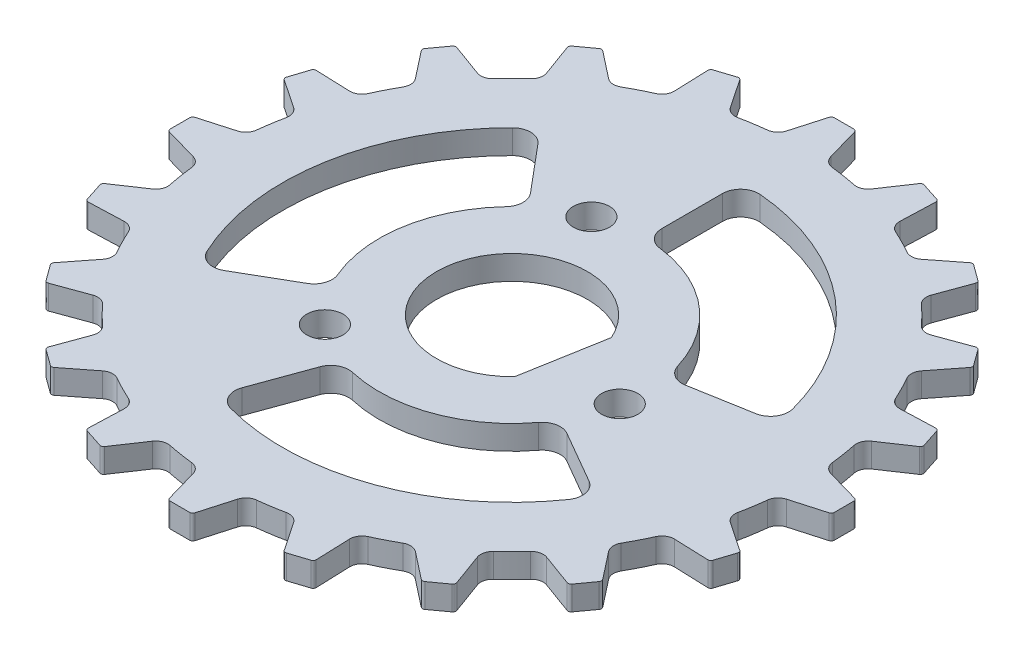
SolidWorks part; units mm, degrees
ref_plane "Front" through (0, 0, 0) normal (0, 0, 1) x (1, 0, 0)
ref_plane "Top" through (0, 0, 0) normal (0, 1, 0) x (1, 0, 0)
ref_plane "Right" through (0, 0, 0) normal (1, 0, 0) x (0, 0, -1)
sketch "草图1" plane through (0, 0, 0) normal (0, 1, 0) x (1, 0, 0)
  line L0 (-0.8114, 27.5) -> (0.8114, 27.5)
  line L3 (1.8377, 24.5681) -> (1.0518, 27.3187)
  line L7 (-1.8377, 24.5681) -> (-1.0518, 27.3187)
  line L8 (7.7263, 26.4048) -> (9.2697, 25.9033)
  line L9 (9.3397, 22.7977) -> (9.4423, 25.6566)
  line L10 (5.8442, 23.9335) -> (7.4416, 26.3066)
  line L11 (15.5076, 22.7249) -> (16.8206, 21.771)
  line L12 (15.9275, 18.7958) -> (16.9084, 21.483)
  line L13 (12.954, 20.9562) -> (15.2066, 22.7195)
  line L14 (21.771, 16.8206) -> (22.7249, 15.5076)
  line L15 (20.9562, 12.954) -> (22.7195, 15.2066)
  line L16 (18.7958, 15.9275) -> (21.483, 16.9084)
  line L17 (25.9033, 9.2697) -> (26.4048, 7.7263)
  line L18 (23.9335, 5.8442) -> (26.3066, 7.4416)
  line L19 (22.7977, 9.3397) -> (25.6566, 9.4423)
  line L20 (27.5, 0.8114) -> (27.5, -0.8114)
  line L21 (24.5681, -1.8377) -> (27.3187, -1.0518)
  line L22 (24.5681, 1.8377) -> (27.3187, 1.0518)
  line L23 (26.4048, -7.7263) -> (25.9033, -9.2697)
  line L24 (22.7977, -9.3397) -> (25.6566, -9.4423)
  line L25 (23.9335, -5.8442) -> (26.3066, -7.4416)
  line L26 (22.7249, -15.5076) -> (21.771, -16.8206)
  line L27 (18.7958, -15.9275) -> (21.483, -16.9084)
  line L28 (20.9562, -12.954) -> (22.7195, -15.2066)
  line L29 (16.8206, -21.771) -> (15.5076, -22.7249)
  line L30 (12.954, -20.9562) -> (15.2066, -22.7195)
  line L31 (15.9275, -18.7958) -> (16.9084, -21.483)
  line L32 (9.2697, -25.9033) -> (7.7263, -26.4048)
  line L33 (5.8442, -23.9335) -> (7.4416, -26.3066)
  line L34 (9.3397, -22.7977) -> (9.4423, -25.6566)
  line L35 (0.8114, -27.5) -> (-0.8114, -27.5)
  line L36 (-1.8377, -24.5681) -> (-1.0518, -27.3187)
  line L37 (1.8377, -24.5681) -> (1.0518, -27.3187)
  line L38 (-7.7263, -26.4048) -> (-9.2697, -25.9033)
  line L39 (-9.3397, -22.7977) -> (-9.4423, -25.6566)
  line L40 (-5.8442, -23.9335) -> (-7.4416, -26.3066)
  line L41 (-15.5076, -22.7249) -> (-16.8206, -21.771)
  line L42 (-15.9275, -18.7958) -> (-16.9084, -21.483)
  line L43 (-12.954, -20.9562) -> (-15.2066, -22.7195)
  line L44 (-21.771, -16.8206) -> (-22.7249, -15.5076)
  line L45 (-20.9562, -12.954) -> (-22.7195, -15.2066)
  line L46 (-18.7958, -15.9275) -> (-21.483, -16.9084)
  line L47 (-25.9033, -9.2697) -> (-26.4048, -7.7263)
  line L48 (-23.9335, -5.8442) -> (-26.3066, -7.4416)
  line L49 (-22.7977, -9.3397) -> (-25.6566, -9.4423)
  line L50 (-27.5, -0.8114) -> (-27.5, 0.8114)
  line L51 (-24.5681, 1.8377) -> (-27.3187, 1.0518)
  line L52 (-24.5681, -1.8377) -> (-27.3187, -1.0518)
  line L53 (-26.4048, 7.7263) -> (-25.9033, 9.2697)
  line L54 (-22.7977, 9.3397) -> (-25.6566, 9.4423)
  line L55 (-23.9335, 5.8442) -> (-26.3066, 7.4416)
  line L56 (-22.7249, 15.5076) -> (-21.771, 16.8206)
  line L57 (-18.7958, 15.9275) -> (-21.483, 16.9084)
  line L58 (-20.9562, 12.954) -> (-22.7195, 15.2066)
  line L59 (-16.8206, 21.771) -> (-15.5076, 22.7249)
  line L60 (-12.954, 20.9562) -> (-15.2066, 22.7195)
  line L61 (-15.9275, 18.7958) -> (-16.9084, 21.483)
  line L62 (-9.2697, 25.9033) -> (-7.7263, 26.4048)
  line L63 (-5.8442, 23.9335) -> (-7.4416, 26.3066)
  line L64 (-9.3397, 22.7977) -> (-9.4423, 25.6566)
  line L65 (0, 19) -> (0, 11)
  line L67 (18.7113, 3.2993) -> (10.8329, 1.9101)
  line L68 (16.4545, -9.5) -> (9.5263, -5.5)
  line L70 (-6.4984, -17.8542) -> (-3.7622, -10.3366)
  line L71 (-16.4545, -9.5) -> (-9.5263, -5.5)
  line L72 (5.1292, -0.9044) -> (5.7291, 2.4979)
  line L73 (-12.213, 14.5548) -> (-7.0707, 8.4265)
  line L74 (12.213, 14.5548) -> (7.0707, 8.4265) [skipped]
  line L75 (6.4984, -17.8542) -> (3.7622, -10.3366) [skipped]
  line L76 (-18.7113, 3.2993) -> (-10.8329, 1.9101) [skipped]
  line L77 (5.1292, -0.9044) -> (4.5293, -4.3067)
  arc A0 (-2.6872, 23.8491) -> (-4.814, 23.5122) centre (0, 0) ccw
  arc A2 (1.8377, 24.5681) -> (2.6872, 23.8491) centre (2.7992, 24.8428) ccw
  arc A3 (-1.8377, 24.5681) -> (-2.6872, 23.8491) centre (-2.7992, 24.8428) cw
  arc A4 (1.0518, 27.3187) -> (0.8114, 27.5) centre (0.8114, 27.25) ccw
  arc A5 (-1.0518, 27.3187) -> (-0.8114, 27.5) centre (-0.8114, 27.25) cw
  arc A6 (7.4416, 26.3066) -> (7.7263, 26.4048) centre (7.649, 26.167) cw
  arc A7 (9.4423, 25.6566) -> (9.2697, 25.9033) centre (9.1924, 25.6655) ccw
  arc A8 (5.8442, 23.9335) -> (4.814, 23.5122) centre (5.0146, 24.4919) cw
  arc A9 (9.3397, 22.7977) -> (9.9255, 21.8514) centre (10.3391, 22.7619) ccw
  arc A10 (15.2066, 22.7195) -> (15.5076, 22.7249) centre (15.3607, 22.5227) cw
  arc A11 (16.9084, 21.483) -> (16.8206, 21.771) centre (16.6736, 21.5688) ccw
  arc A12 (12.954, 20.9562) -> (11.8441, 20.8738) centre (12.3376, 21.7436) cw
  arc A13 (15.9275, 18.7958) -> (16.1922, 17.7148) centre (16.8668, 18.4529) ccw
  arc A14 (21.483, 16.9084) -> (21.771, 16.8206) centre (21.5688, 16.6736) cw
  arc A15 (22.7195, 15.2066) -> (22.7249, 15.5076) centre (22.5227, 15.3607) ccw
  arc A16 (18.7958, 15.9275) -> (17.7148, 16.1922) centre (18.4529, 16.8668) cw
  arc A17 (20.9562, 12.954) -> (20.8738, 11.8441) centre (21.7436, 12.3376) ccw
  arc A18 (25.6566, 9.4423) -> (25.9033, 9.2697) centre (25.6655, 9.1924) cw
  arc A19 (26.3066, 7.4416) -> (26.4048, 7.7263) centre (26.167, 7.649) ccw
  arc A20 (22.7977, 9.3397) -> (21.8514, 9.9255) centre (22.7619, 10.3391) cw
  arc A21 (23.9335, 5.8442) -> (23.5122, 4.814) centre (24.4919, 5.0146) ccw
  arc A22 (27.3187, 1.0518) -> (27.5, 0.8114) centre (27.25, 0.8114) cw
  arc A23 (27.3187, -1.0518) -> (27.5, -0.8114) centre (27.25, -0.8114) ccw
  arc A24 (24.5681, 1.8377) -> (23.8491, 2.6872) centre (24.8428, 2.7992) cw
  arc A25 (24.5681, -1.8377) -> (23.8491, -2.6872) centre (24.8428, -2.7992) ccw
  arc A26 (26.3066, -7.4416) -> (26.4048, -7.7263) centre (26.167, -7.649) cw
  arc A27 (25.6566, -9.4423) -> (25.9033, -9.2697) centre (25.6655, -9.1924) ccw
  arc A28 (23.9335, -5.8442) -> (23.5122, -4.814) centre (24.4919, -5.0146) cw
  arc A29 (22.7977, -9.3397) -> (21.8514, -9.9255) centre (22.7619, -10.3391) ccw
  arc A30 (22.7195, -15.2066) -> (22.7249, -15.5076) centre (22.5227, -15.3607) cw
  arc A31 (21.483, -16.9084) -> (21.771, -16.8206) centre (21.5688, -16.6736) ccw
  arc A32 (20.9562, -12.954) -> (20.8738, -11.8441) centre (21.7436, -12.3376) cw
  arc A33 (18.7958, -15.9275) -> (17.7148, -16.1922) centre (18.4529, -16.8668) ccw
  arc A34 (16.9084, -21.483) -> (16.8206, -21.771) centre (16.6736, -21.5688) cw
  arc A35 (15.2066, -22.7195) -> (15.5076, -22.7249) centre (15.3607, -22.5227) ccw
  arc A36 (15.9275, -18.7958) -> (16.1922, -17.7148) centre (16.8668, -18.4529) cw
  arc A37 (12.954, -20.9562) -> (11.8441, -20.8738) centre (12.3376, -21.7436) ccw
  arc A38 (9.4423, -25.6566) -> (9.2697, -25.9033) centre (9.1924, -25.6655) cw
  arc A39 (7.4416, -26.3066) -> (7.7263, -26.4048) centre (7.649, -26.167) ccw
  arc A40 (9.3397, -22.7977) -> (9.9255, -21.8514) centre (10.3391, -22.7619) cw
  arc A41 (5.8442, -23.9335) -> (4.814, -23.5122) centre (5.0146, -24.4919) ccw
  arc A42 (1.0518, -27.3187) -> (0.8114, -27.5) centre (0.8114, -27.25) cw
  arc A43 (-1.0518, -27.3187) -> (-0.8114, -27.5) centre (-0.8114, -27.25) ccw
  arc A44 (1.8377, -24.5681) -> (2.6872, -23.8491) centre (2.7992, -24.8428) cw
  arc A45 (-1.8377, -24.5681) -> (-2.6872, -23.8491) centre (-2.7992, -24.8428) ccw
  arc A46 (-7.4416, -26.3066) -> (-7.7263, -26.4048) centre (-7.649, -26.167) cw
  arc A47 (-9.4423, -25.6566) -> (-9.2697, -25.9033) centre (-9.1924, -25.6655) ccw
  arc A48 (-5.8442, -23.9335) -> (-4.814, -23.5122) centre (-5.0146, -24.4919) cw
  arc A49 (-9.3397, -22.7977) -> (-9.9255, -21.8514) centre (-10.3391, -22.7619) ccw
  arc A50 (-15.2066, -22.7195) -> (-15.5076, -22.7249) centre (-15.3607, -22.5227) cw
  arc A51 (-16.9084, -21.483) -> (-16.8206, -21.771) centre (-16.6736, -21.5688) ccw
  arc A52 (-12.954, -20.9562) -> (-11.8441, -20.8738) centre (-12.3376, -21.7436) cw
  arc A53 (-15.9275, -18.7958) -> (-16.1922, -17.7148) centre (-16.8668, -18.4529) ccw
  arc A54 (-21.483, -16.9084) -> (-21.771, -16.8206) centre (-21.5688, -16.6736) cw
  arc A55 (-22.7195, -15.2066) -> (-22.7249, -15.5076) centre (-22.5227, -15.3607) ccw
  arc A56 (-18.7958, -15.9275) -> (-17.7148, -16.1922) centre (-18.4529, -16.8668) cw
  arc A57 (-20.9562, -12.954) -> (-20.8738, -11.8441) centre (-21.7436, -12.3376) ccw
  arc A58 (-25.6566, -9.4423) -> (-25.9033, -9.2697) centre (-25.6655, -9.1924) cw
  arc A59 (-26.3066, -7.4416) -> (-26.4048, -7.7263) centre (-26.167, -7.649) ccw
  arc A60 (-22.7977, -9.3397) -> (-21.8514, -9.9255) centre (-22.7619, -10.3391) cw
  arc A61 (-23.9335, -5.8442) -> (-23.5122, -4.814) centre (-24.4919, -5.0146) ccw
  arc A62 (-27.3187, -1.0518) -> (-27.5, -0.8114) centre (-27.25, -0.8114) cw
  arc A63 (-27.3187, 1.0518) -> (-27.5, 0.8114) centre (-27.25, 0.8114) ccw
  arc A64 (-24.5681, -1.8377) -> (-23.8491, -2.6872) centre (-24.8428, -2.7992) cw
  arc A65 (-24.5681, 1.8377) -> (-23.8491, 2.6872) centre (-24.8428, 2.7992) ccw
  arc A66 (-26.3066, 7.4416) -> (-26.4048, 7.7263) centre (-26.167, 7.649) cw
  arc A67 (-25.6566, 9.4423) -> (-25.9033, 9.2697) centre (-25.6655, 9.1924) ccw
  arc A68 (-23.9335, 5.8442) -> (-23.5122, 4.814) centre (-24.4919, 5.0146) cw
  arc A69 (-22.7977, 9.3397) -> (-21.8514, 9.9255) centre (-22.7619, 10.3391) ccw
  arc A70 (-22.7195, 15.2066) -> (-22.7249, 15.5076) centre (-22.5227, 15.3607) cw
  arc A71 (-21.483, 16.9084) -> (-21.771, 16.8206) centre (-21.5688, 16.6736) ccw
  arc A72 (-20.9562, 12.954) -> (-20.8738, 11.8441) centre (-21.7436, 12.3376) cw
  arc A73 (-18.7958, 15.9275) -> (-17.7148, 16.1922) centre (-18.4529, 16.8668) ccw
  arc A74 (-16.9084, 21.483) -> (-16.8206, 21.771) centre (-16.6736, 21.5688) cw
  arc A75 (-15.2066, 22.7195) -> (-15.5076, 22.7249) centre (-15.3607, 22.5227) ccw
  arc A76 (-15.9275, 18.7958) -> (-16.1922, 17.7148) centre (-16.8668, 18.4529) cw
  arc A77 (-12.954, 20.9562) -> (-11.8441, 20.8738) centre (-12.3376, 21.7436) ccw
  arc A78 (-9.4423, 25.6566) -> (-9.2697, 25.9033) centre (-9.1924, 25.6655) cw
  arc A79 (-7.4416, 26.3066) -> (-7.7263, 26.4048) centre (-7.649, 26.167) ccw
  arc A80 (-9.3397, 22.7977) -> (-9.9255, 21.8514) centre (-10.3391, 22.7619) cw
  arc A81 (-5.8442, 23.9335) -> (-4.814, 23.5122) centre (-5.0146, 24.4919) ccw
  arc A82 (-9.9255, 21.8514) -> (-11.8441, 20.8738) centre (0, 0) ccw
  arc A83 (-16.1922, 17.7148) -> (-17.7148, 16.1922) centre (0, 0) ccw
  arc A84 (-20.8738, 11.8441) -> (-21.8514, 9.9255) centre (0, 0) ccw
  arc A85 (-23.5122, 4.814) -> (-23.8491, 2.6872) centre (0, 0) ccw
  arc A86 (-23.8491, -2.6872) -> (-23.5122, -4.814) centre (0, 0) ccw
  arc A87 (4.814, 23.5122) -> (2.6872, 23.8491) centre (0, 0) ccw
  arc A88 (11.8441, 20.8738) -> (9.9255, 21.8514) centre (0, 0) ccw
  arc A89 (17.7148, 16.1922) -> (16.1922, 17.7148) centre (0, 0) ccw
  arc A90 (21.8514, 9.9255) -> (20.8738, 11.8441) centre (0, 0) ccw
  arc A91 (23.8491, 2.6872) -> (23.5122, 4.814) centre (0, 0) ccw
  arc A92 (23.5122, -4.814) -> (23.8491, -2.6872) centre (0, 0) ccw
  arc A93 (20.8738, -11.8441) -> (21.8514, -9.9255) centre (0, 0) ccw
  arc A94 (16.1922, -17.7148) -> (17.7148, -16.1922) centre (0, 0) ccw
  arc A95 (9.9255, -21.8514) -> (11.8441, -20.8738) centre (0, 0) ccw
  arc A96 (-4.814, -23.5122) -> (-2.6872, -23.8491) centre (0, 0) ccw
  arc A97 (2.6872, -23.8491) -> (4.814, -23.5122) centre (0, 0) ccw
  arc A98 (-11.8441, -20.8738) -> (-9.9255, -21.8514) centre (0, 0) ccw
  arc A99 (-17.7148, -16.1922) -> (-16.1922, -17.7148) centre (0, 0) ccw
  arc A100 (-21.8514, -9.9255) -> (-20.8738, -11.8441) centre (0, 0) ccw
  arc A101 (-7.0707, 8.4265) -> (-9.5263, -5.5) centre (0, 0) ccw
  arc A102 (-12.213, 14.5548) -> (-16.4545, -9.5) centre (0, 0) ccw
  arc A103 (-6.4984, -17.8542) -> (16.4545, -9.5) centre (0, 0) ccw
  arc A104 (18.7113, 3.2993) -> (0, 19) centre (0, 0) ccw
  arc A105 (-3.7622, -10.3366) -> (9.5263, -5.5) centre (0, 0) ccw
  arc A106 (10.8329, 1.9101) -> (0, 11) centre (0, 0) ccw
  arc A107 (5.7291, 2.4979) -> (4.5293, -4.3067) centre (0, 0) ccw
  circle A111 centre (-3.7622, 10.3366) radius 1.5
  circle A112 centre (10.8329, -1.9101) radius 1.5
  circle A113 centre (-7.0707, -8.4265) radius 1.5
  point P245 (0, 0)
  point P266 (0, 0)
  dimension "D1" = 20
  dimension "D2" = 9
extrude "凸台-拉伸1" add sketch "草图1" along normal blind 2
fillet "圆角1" radius 1.5 12 edges at (-3.7622, 1, 10.3366) (-6.4984, 1, 17.8542) (16.4545, 1, 9.5) (9.5263, 1, 5.5) (18.7113, 1, -3.2993) (10.8329, 1, -1.9101) (-12.213, 1, -14.5548) (-9.5263, 1, 5.5) (-7.0707, 1, -8.4265) (-16.4545, 1, 9.5) (0, 1, -11) (0, 1, -19)
